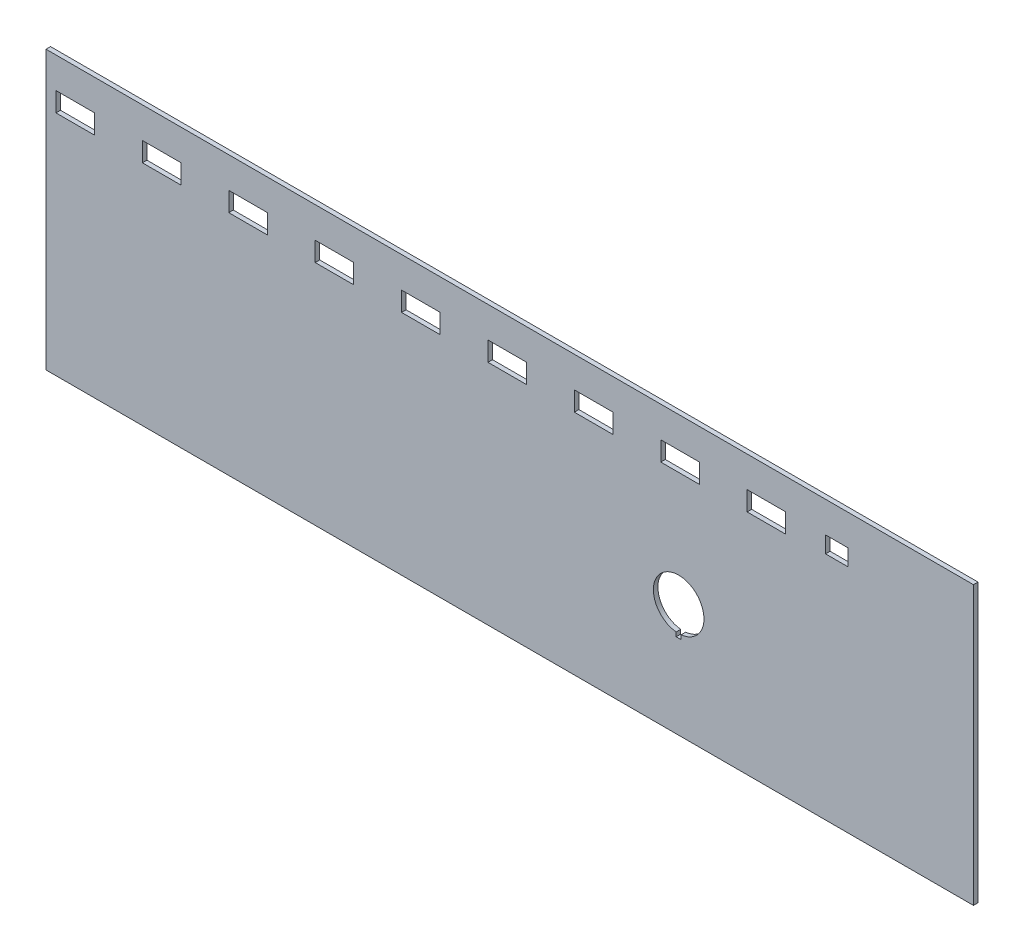
SolidWorks part; units mm, degrees
ref_plane "Front Plane" through (0, 0, 0) normal (0, 0, 1) x (1, 0, 0)
ref_plane "Top Plane" through (0, 0, 0) normal (0, 1, 0) x (1, 0, 0)
ref_plane "Right Plane" through (0, 0, 0) normal (1, 0, 0) x (0, 0, -1)
sketch "Sketch1" plane through (0, 0, 0) normal (0, 0, 1) x (1, 0, 0)
  line L1 (0, 0) -> (409, 0)
  line L2 (0, 0) -> (0, -122.5)
  line L3 (0, -122.5) -> (409, -122.5)
  line L4 (409, 0) -> (409, -122.5)
  dimension "D1" = 409
  dimension "D2" = 122.5
extrude "Boss-Extrude1" add sketch "Sketch1" along normal blind 2
sketch "Sketch2" plane through (0, 0, 2) normal (0, 0, 1) x (1, 0, 0)
  line L2 (0, 0) -> (409, 0)
  line L3 (0, 0) -> (0, -122.5)
  line L4 (0, -122.5) -> (409, -122.5)
  line L5 (409, 0) -> (409, -122.5)
  line L6 (353.775, -20.85) -> (343.775, -20.85)
  line L7 (353.775, -20.85) -> (353.775, -13.6)
  line L8 (353.775, -13.6) -> (343.775, -13.6)
  line L9 (343.775, -20.85) -> (343.775, -13.6)
  line L12 (326.2, -22.13) -> (309.2, -22.13)
  line L13 (326.2, -22.13) -> (326.2, -13.6)
  line L14 (326.2, -13.6) -> (309.2, -13.6)
  line L15 (309.2, -22.13) -> (309.2, -13.6)
  line L18 (288.1, -22.13) -> (288.1, -13.6)
  line L19 (288.1, -22.13) -> (271.1, -22.13)
  line L20 (271.1, -22.13) -> (271.1, -13.6)
  line L21 (288.1, -13.6) -> (271.1, -13.6)
  line L22 (250, -22.13) -> (250, -13.6)
  line L23 (250, -22.13) -> (233, -22.13)
  line L24 (233, -22.13) -> (233, -13.6)
  line L25 (250, -13.6) -> (233, -13.6)
  line L26 (211.9, -22.13) -> (211.9, -13.6)
  line L27 (211.9, -22.13) -> (194.9, -22.13)
  line L28 (194.9, -22.13) -> (194.9, -13.6)
  line L29 (211.9, -13.6) -> (194.9, -13.6)
  line L30 (173.8, -22.13) -> (173.8, -13.6)
  line L31 (173.8, -22.13) -> (156.8, -22.13)
  line L32 (156.8, -22.13) -> (156.8, -13.6)
  line L33 (173.8, -13.6) -> (156.8, -13.6)
  line L34 (135.7, -22.13) -> (135.7, -13.6)
  line L35 (135.7, -22.13) -> (118.7, -22.13)
  line L36 (118.7, -22.13) -> (118.7, -13.6)
  line L37 (135.7, -13.6) -> (118.7, -13.6)
  line L38 (97.6, -22.13) -> (97.6, -13.6)
  line L39 (97.6, -22.13) -> (80.6, -22.13)
  line L40 (80.6, -22.13) -> (80.6, -13.6)
  line L41 (97.6, -13.6) -> (80.6, -13.6)
  line L42 (59.5, -22.13) -> (59.5, -13.6)
  line L43 (59.5, -22.13) -> (42.5, -22.13)
  line L44 (42.5, -22.13) -> (42.5, -13.6)
  line L45 (59.5, -13.6) -> (42.5, -13.6)
  line L46 (21.4, -22.13) -> (21.4, -13.6)
  line L47 (21.4, -22.13) -> (4.4, -22.13)
  line L48 (4.4, -22.13) -> (4.4, -13.6)
  line L49 (21.4, -13.6) -> (4.4, -13.6)
  line L50 (277.9, -83.5956) -> (277.9, -85.45)
  line L51 (277.9, -85.45) -> (280.1, -85.45)
  line L52 (280.1, -85.45) -> (280.1, -83.5956)
  arc A1 (280.1, -83.5956) -> (277.9, -83.5956) centre (279, -72.5) ccw
  point P6 (0, 0)
  point P7 (0, 0)
  point P10 (409, 0)
  point P29 (317.7, -22.13)
  point P37 (279.6, -22.13)
  point P71 (254.5002, -83.0826)
  point P76 (252.4251, -48.3042)
  point P77 (279, -85.45)
  point P78 (279, -61.35)
  point P79 (252.393, -57.273)
  dimension "D10" = 22.3
  dimension "D1" = 10
  dimension "D2" = 82.8
  dimension "D3" = 13.6
  dimension "D4" = 17
  dimension "D8" = 38.1
  dimension "D9" = 2.2
  dimension "D11" = 24.1
  dimension "D12" = 130
  dimension "D13" = 50
  dimension "D14" = 8.53
  dimension "D15" = 122.5
  dimension "D16" = 409
  dimension "D17" = 55.225
  dimension "D18" = 20.85
  dimension "D19" = 7.25
  dimension "D7" = 9
extrude "Cut-Extrude2" cut sketch "Sketch2" against normal through all both and the other way through all contours L46 L49 L48 L47 | L42 L45 L44 L43 | L38 L41 L40 L39 | L34 L37 L36 L35 | L30 L33 L32 L31 | L26 L29 L28 L27 | L18 L21 L20 L19 | L22 L25 L24 L23 | L15 L12 L13 L14 | L9 L6 L7 L8 | L52 A1 L50 L51
